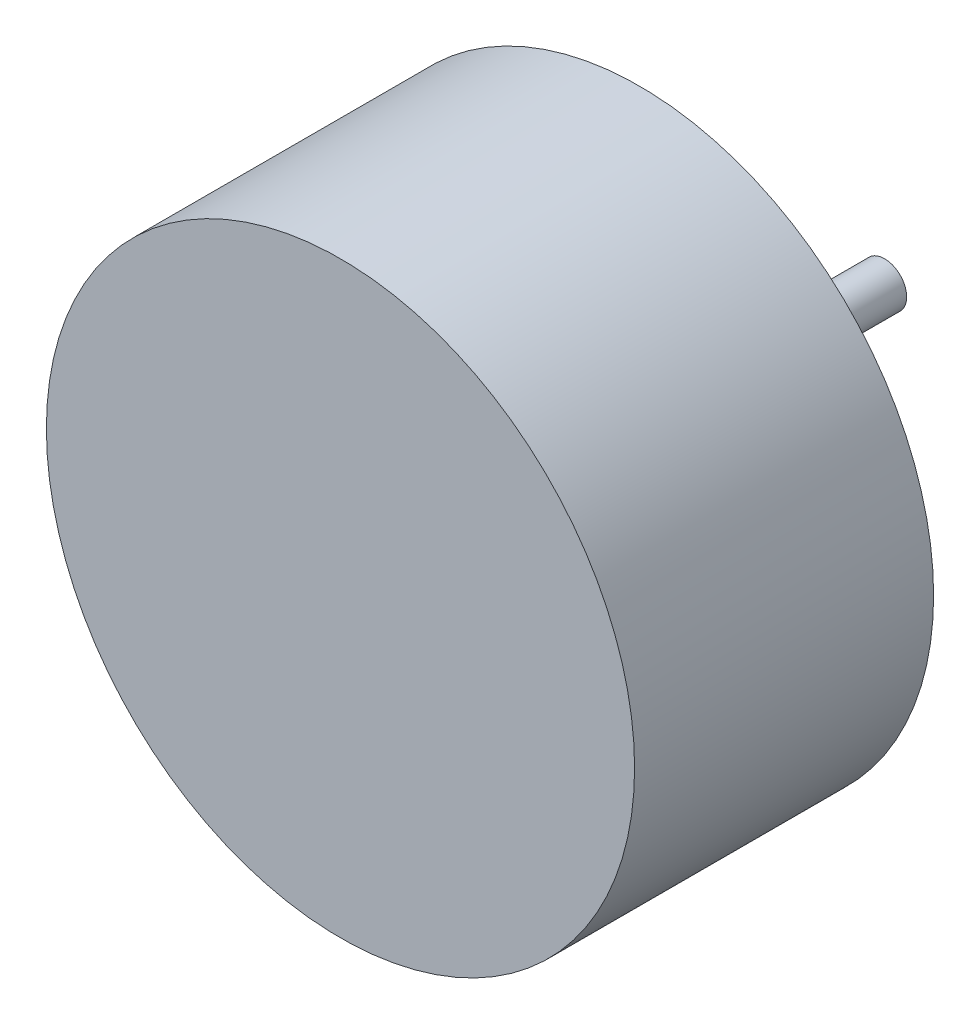
SolidWorks part; units mm, degrees
ref_plane "前视基准面" through (0, 0, 0) normal (0, 0, 1) x (1, 0, 0)
ref_plane "上视基准面" through (0, 0, 0) normal (0, 1, 0) x (1, 0, 0)
ref_plane "右视基准面" through (0, 0, 0) normal (1, 0, 0) x (0, 0, -1)
sketch "草图1" plane through (0, 0, 0) normal (0, 0, 1) x (1, 0, 0)
  circle A0 centre (0, 0) radius 12
extrude "凸台-拉伸1" add sketch "草图1" along normal blind 12.2
sketch "草图2" plane through (0, 0, 0) normal (0, 0, -1) x (-1, 0, 0)
  circle A0 centre (0, 0) radius 0.9
extrude "凸台-拉伸2" add sketch "草图2" along normal blind 10
